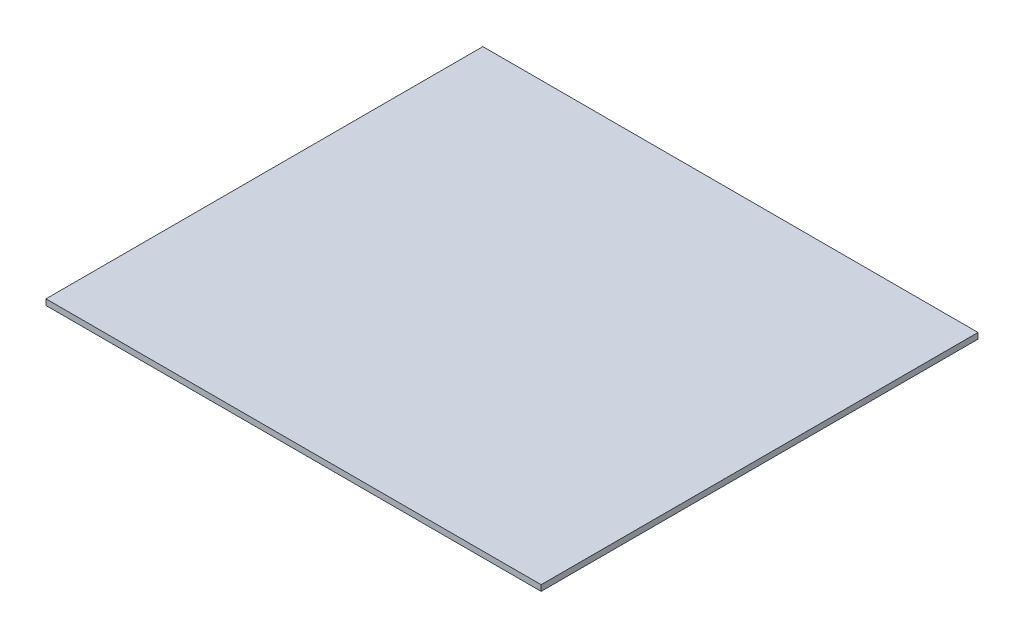
SolidWorks part; units mm, degrees
material "Сосна"
ref_plane "Спереди" through (0, 0, 0) normal (0, 0, 1) x (1, 0, 0)
ref_plane "Сверху" through (0, 0, 0) normal (0, 1, 0) x (1, 0, 0)
ref_plane "Справа" through (0, 0, 0) normal (1, 0, 0) x (0, 0, -1)
sketch3d "Трехмерный эскиз1"
  line L1 (-117.416, 10, 146.6656) -> (222.584, 10, 146.6656)
  line L2 (-117.416, 10, 146.6656) -> (-117.416, 10, -153.3344)
  line L3 (-117.416, 10, -153.3344) -> (222.584, 10, -153.3344)
  line L4 (222.584, 10, 146.6656) -> (222.584, 10, -153.3344)
  dimension "D1" = 10
  dimension "D2" = 300
  dimension "D3" = 340
extrude "Бобышка-Вытянуть1" add sketch "Трехмерный эскиз1" along direction (0, 1, 0) on the side of the normal blind 4
